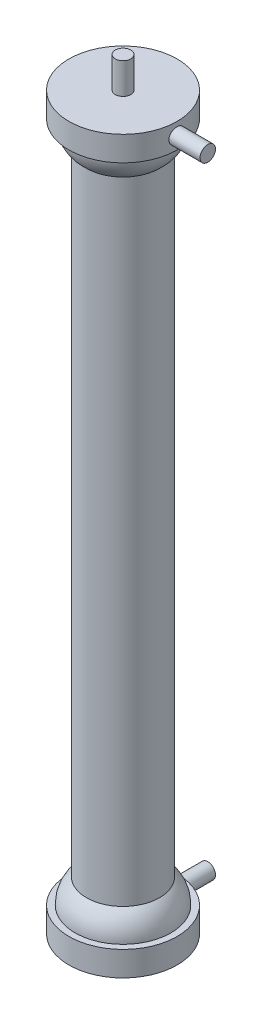
SolidWorks part; units mm, degrees
ref_plane "Front Plane" through (0, 0, 0) normal (0, 0, 1) x (1, 0, 0)
ref_plane "Top Plane" through (0, 0, 0) normal (0, 1, 0) x (1, 0, 0)
ref_plane "Right Plane" through (0, 0, 0) normal (1, 0, 0) x (0, 0, -1)
sketch "Sketch1" plane through (0, 0, 0) normal (0, 0, 1) x (1, 0, 0)
  line L1 (15, 33.02) -> (15, 292.38)
  line L4 (0, -1025.4) -> (0, 0) construction
  line L5 (19.685, 302.54) -> (22.225, 302.54)
  line L6 (22.225, 302.54) -> (22.225, 312.7)
  line L7 (19.685, 22.86) -> (22.225, 22.86)
  line L8 (22.225, 22.86) -> (22.225, 12.7)
  line L9 (3.175, 12.7) -> (22.225, 12.7)
  line L10 (3.175, 312.7) -> (22.225, 312.7)
  line L11 (3.175, 12.7) -> (3.175, 0)
  line L12 (3.175, 0) -> (0, 0)
  line L14 (0, -1333.3322) -> (0, 0) construction
  line L15 (3.175, 312.7) -> (3.175, 325.4)
  line L16 (3.175, 325.4) -> (0, 325.4)
  line L18 (0, 325.4) -> (0, 50000) construction
  line L20 (0, 325.4) -> (0, 0)
  arc A0 (19.685, 22.86) -> (15, 33.02) centre (6.9887, 23.1656) ccw
  arc A1 (19.685, 302.54) -> (15, 292.38) centre (6.9887, 302.2344) cw
  point P2 (0, 0)
  point P5 (3.175, 302.3295)
  dimension "D5" = 12.7
  dimension "D7" = 2.54
  dimension "D1" = 44.45
  dimension "D2" = 30
  dimension "D3" = 300
  dimension "D4" = 10.16
  dimension "D6" = 10.16
  dimension "D8" = 10.16
  dimension "D9" = 12.7
  dimension "D10" = 6.35
revolve "Revolve1" add sketch "Sketch1" angle 360 about L4
sketch "Sketch2" plane through (0, 0, 0) normal (1, 0, 0) x (0, 0, -1)
  line L0 (0, 312.7) -> (0, 302.54) construction
  line L1 (22.225, 312.7) -> (-22.225, 312.7) construction
  line L2 (-19.685, 302.54) -> (19.685, 302.54) construction
  circle A0 centre (0, 307.62) radius 3.175
  point P8 (4.0247, 307.2086)
  point P9 (0, 307.62)
  dimension "D1" = 6.35
extrude "Boss-Extrude1" add sketch "Sketch2" along normal blind 34.798
sketch "Sketch3" plane through (0, 0, 0) normal (0, 0, 1) x (1, 0, 0)
  line L0 (0, 12.7) -> (0, 22.86) construction
  line L1 (-3.175, 12.7) -> (3.175, 12.7) construction
  line L2 (22.225, 22.86) -> (-22.225, 22.86) construction
  circle A0 centre (0, 17.78) radius 3.175
  point P8 (4.2313, 17.4695)
  point P9 (0, 17.78)
  dimension "D1" = 6.35
extrude "Boss-Extrude2" add sketch "Sketch3" against normal blind 34.798
